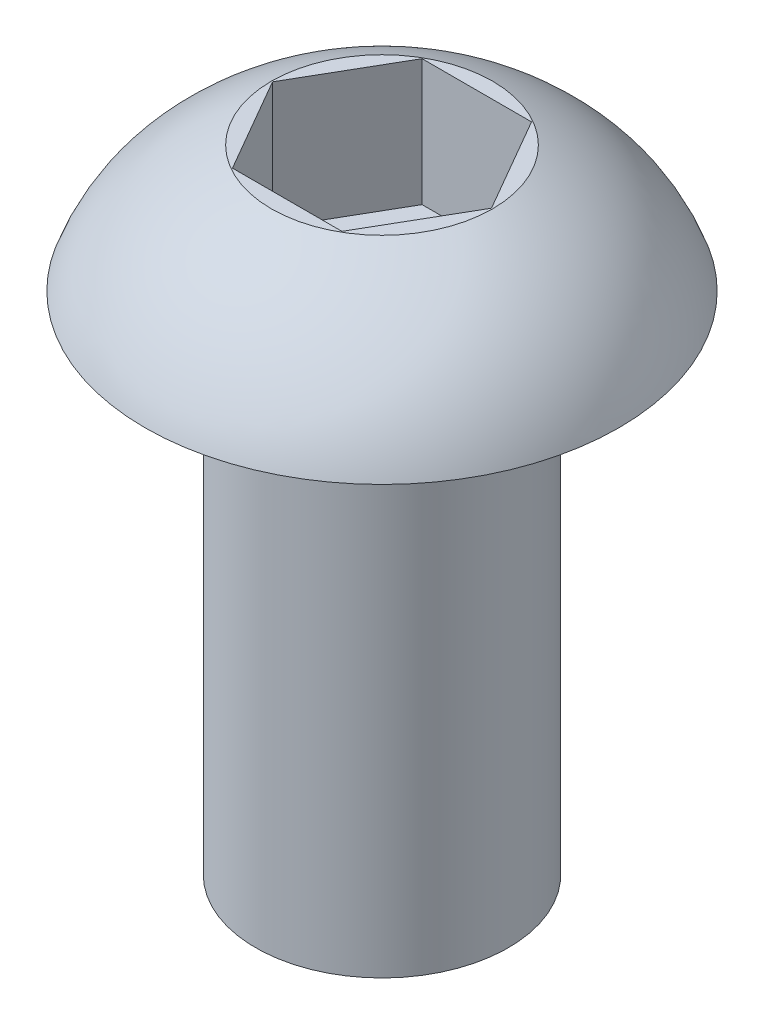
SolidWorks part; units mm, degrees
ref_plane "前视基准面" through (0, 0, 0) normal (0, 0, 1) x (1, 0, 0)
ref_plane "上视基准面" through (0, 0, 0) normal (0, 1, 0) x (1, 0, 0)
ref_plane "右视基准面" through (0, 0, 0) normal (1, 0, 0) x (0, 0, -1)
other "Configuration Table"
sketch "Sketch15" plane through (0, 0, 0) normal (1, 0, 0) x (0, 0, -1)
  line L0 (-1, -4) -> (-1, 4)
  line L1 (-1, 4) -> (1, 4)
  line L2 (-1, 4) -> (-1, -4)
  line L3 (-1, -4) -> (1, -4)
  line L4 (1, 4) -> (1, -4)
  line L5 (-1, 4) -> (1, -4) construction
  line L6 (-1, -4) -> (1, 4) construction
  line L7 (1, 4) -> (2.75, 4)
  line L8 (-1, 4) -> (0.75, 4)
  line L9 (0.75, 4) -> (0.75, 6)
  spline S0 degree 2 poles (0.75, 6) (2.291, 5.3196) (2.75, 4) knots 0 0 0 0.856056 0.856056 0.856056
  point P0 (0, 0)
  dimension "D1" = 8
  dimension "D2" = 2
  dimension "D3" = 3.75
  dimension "D4" = 1.75
  dimension "D5" = 2
revolve "Revolve3" add sketch "Sketch15" angle 360 about L0
ref_plane "Plane4" through (0, 4, 0) normal (0, 1, 0) x (1, 0, 0)
sketch "Sketch19" plane through (0, 4, 0) normal (0, 1, 0) x (1, 0, 0)
  line L1 (1.7321, -1) -> (0.866, 0.5)
  line L2 (0.866, 0.5) -> (-0.866, 0.5)
  line L3 (-0.866, 0.5) -> (-1.7321, -1)
  line L4 (-1.7321, -1) -> (-0.866, -2.5)
  line L5 (-0.866, -2.5) -> (0.866, -2.5)
  line L6 (0.866, -2.5) -> (1.7321, -1)
  circle A0 centre (0, -1) radius 1.5 construction
  circle A1 centre (0, -1) radius 1.75
  dimension "D1" = 3
extrude "Boss-Extrude11" add sketch "Sketch19" along normal blind 2
